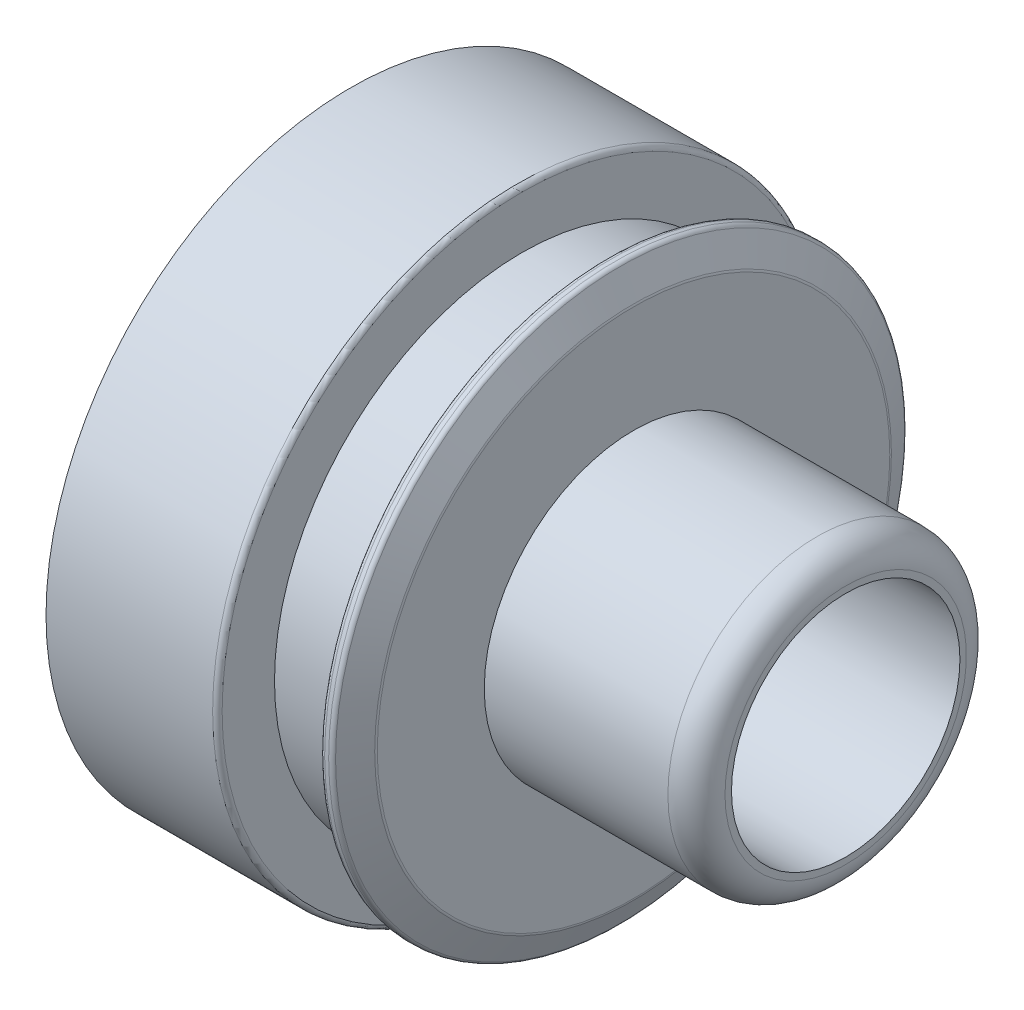
SolidWorks part; units mm, degrees
ref_plane "Alzado" through (0, 0, 0) normal (0, 0, 1) x (1, 0, 0)
ref_plane "Planta" through (0, 0, 0) normal (0, 1, 0) x (1, 0, 0)
ref_plane "Vista lateral" through (0, 0, 0) normal (1, 0, 0) x (0, 0, -1)
sketch "Croquis1" plane through (0, 0, 0) normal (0, 1, 0) x (1, 0, 0)
  line L0 (0, 0) -> (0, 16) construction
  line L1 (0, 0) -> (0, -16) construction
  line L2 (168.6172, 364.9885) -> (1079.2839, 364.9885) construction
  line L3 (0, 0) -> (24.561, 0) construction
  line L4 (0, 5) -> (1.25, 5)
  line L5 (1.5, 4.75) -> (1.5, 4)
  line L6 (1.5, 4) -> (14.5, 4)
  line L7 (14.5, 4) -> (14.5, 6)
  line L8 (14.5, 6) -> (26.5, 6)
  line L9 (26.5, 6) -> (26.5, 6.34)
  line L10 (25, 7.84) -> (15.357, 7.84)
  line L11 (15.357, 7.84) -> (15.357, 13.4584)
  line L12 (15.3311, 13.5692) -> (14.6517, 14.9442)
  line L13 (14.4275, 15.0834) -> (14.2162, 15.0834)
  line L14 (13.9662, 14.8334) -> (13.9662, 13.0003)
  line L15 (13.9662, 13.0003) -> (9.5, 13.0003)
  line L16 (9.5, 13.0003) -> (9.5, 15.75)
  line L17 (9.25, 16) -> (0.5, 16)
  line L18 (0.5, 16) -> (0.5, 15.15)
  line L19 (0.5, 15.15) -> (1.5546, 15.15)
  line L20 (1.5546, 15.15) -> (1.5546, 10.66)
  line L21 (1.3046, 10.41) -> (0, 10.41)
  line L22 (0, 10.41) -> (0, 8.2726)
  line L23 (0, 8.2726) -> (1.5546, 8.2726)
  line L24 (1.5546, 8.2726) -> (1.5546, 7.0128)
  line L25 (1.5546, 7.0128) -> (0, 7.0128)
  line L26 (0, 7.0128) -> (0, 5)
  arc A0 (25, 7.84) -> (26.5, 6.34) centre (25, 6.34) cw
  arc A1 (15.3311, 13.5692) -> (15.357, 13.4584) centre (15.107, 13.4584) cw
  arc A2 (14.4275, 15.0834) -> (14.6517, 14.9442) centre (14.4275, 14.8334) cw
  arc A3 (14.2162, 15.0834) -> (13.9662, 14.8334) centre (14.2162, 14.8334) ccw
  arc A4 (1.5, 4.75) -> (1.25, 5) centre (1.25, 4.75) ccw
  arc A5 (1.5546, 10.66) -> (1.3046, 10.41) centre (1.3046, 10.66) cw
  arc A6 (9.5, 15.75) -> (9.25, 16) centre (9.25, 15.75) ccw
  dimension "D3" = 1.5
  dimension "D4" = 0.25
  dimension "D5" = 0.25
  dimension "D6" = 0.25
  dimension "D23" = 0.25
  dimension "D32" = 0.25
  dimension "D1" = 16
  dimension "D2" = 16
  dimension "D7" = 6
  dimension "D8" = 1.84
  dimension "D9" = 2
  dimension "D10" = 13
  dimension "D11" = 12
  dimension "D12" = 16
  dimension "D13" = 0.85
  dimension "D14" = 4.74
  dimension "D15" = 0.5
  dimension "D17" = 1
  dimension "D18" = 1.5
  dimension "D19" = 4.4662
  dimension "D20" = 1.8331
  dimension "D21" = 5.6184
  dimension "D22" = 1.5337
  dimension "D24" = 0.2113
  dimension "D25" = 153.704
  dimension "D26" = 1.2598
  dimension "D28" = 9
  dimension "D29" = 2.9997
  dimension "D30" = 1.3908
revolve "Revolución1" add sketch "Croquis1" angle 360 about L3
